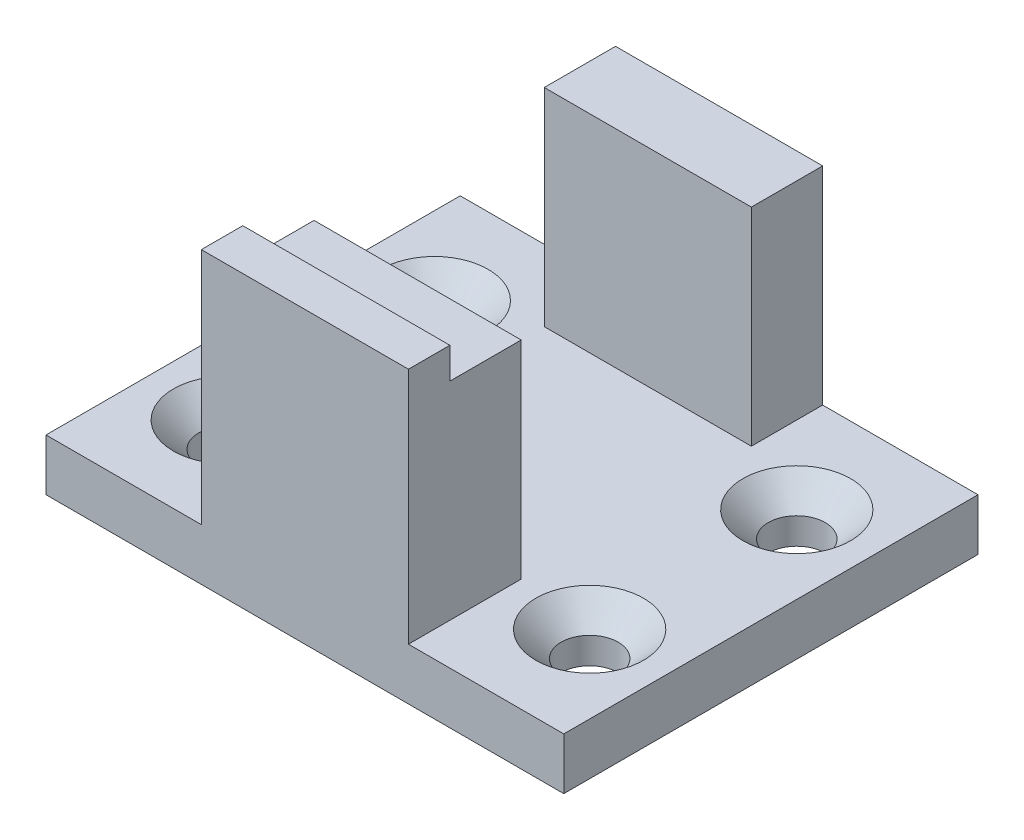
SolidWorks part; units mm, degrees
ref_plane "Front Plane" through (0, 0, 0) normal (0, 0, 1) x (1, 0, 0)
ref_plane "Top Plane" through (0, 0, 0) normal (0, 1, 0) x (1, 0, 0)
ref_plane "Right Plane" through (0, 0, 0) normal (1, 0, 0) x (0, 0, -1)
sketch "Sketch1" plane through (0, 0, 0) normal (0, 1, 0) x (1, 0, 0)
  line L1 (0, 0) -> (20, 0)
  line L2 (0, 0) -> (0, -40)
  line L3 (0, -40) -> (20, -40)
  line L4 (20, 0) -> (20, -40)
  dimension "D1" = 40
  dimension "D2" = 20
extrude "Boss-Extrude1" add sketch "Sketch1" along normal blind 25
sketch "Sketch2" plane through (0, 25, 0) normal (0, 1, 0) x (1, 0, 0)
  line L0 (20, -40) -> (20, 0) construction
  line L1 (0, -40) -> (20, -40)
  line L2 (0, -40) -> (0, -36)
  line L3 (0, -36) -> (20, -36)
  line L4 (20, -40) -> (20, -36)
  dimension "D1" = 4
extrude "Boss-Extrude2" add sketch "Sketch2" along normal blind 3
sketch "Sketch3" plane through (0, 0, 0) normal (-1, 0, 0) x (0, 0, 1)
  line L0 (0, 25) -> (36, 25) construction
  line L1 (0, 25) -> (36, 25)
  line L3 (6.885, 25) -> (29.115, 25)
  line L4 (6.885, 25) -> (6.885, 5)
  line L5 (6.885, 5) -> (29.115, 5)
  line L6 (29.115, 25) -> (29.115, 5)
  point P6 (18, 25)
  point P7 (18, 25)
  dimension "D1" = 22.23
  dimension "D2" = 20
extrude "Cut-Extrude1" cut sketch "Sketch3" against normal up to surface (20 mm away) contours L6 L1 L4 L5 up to face at (20, 17.6667, 25.3333)
sketch "Sketch4" plane through (0, 0, 0) normal (0, 1, 0) x (1, 0, 0)
  line L0 (0, 0) -> (0, -40) construction
  line L1 (0, 0) -> (0, -40)
  line L3 (0, 0) -> (-15, 0)
  line L4 (0, 0) -> (0, -40)
  line L5 (0, -40) -> (-15, -40)
  line L6 (-15, 0) -> (-15, -40)
  dimension "D1" = 15
extrude "Boss-Extrude3" add sketch "Sketch4" along normal up to surface (5 mm away) contours L3 L6 L5 L1 up to face at (10, 5, 18)
sketch "Sketch5" plane through (0, 5, 0) normal (0, 1, 0) x (1, 0, 0)
  line L0 (0, 0) -> (0, -40) construction
  line L1 (0, 0) -> (0, -40) construction
  line L2 (0, 0) -> (-15, 0) construction
  line L3 (-15, 0) -> (-15, -40) construction
  line L4 (0, -40) -> (-15, -40) construction
  line L5 (0, 0) -> (0, -40)
  line L6 (0, 0) -> (0, -40)
  line L7 (0, 0) -> (-15, 0)
  line L8 (-15, 0) -> (-15, -40)
  line L9 (0, -40) -> (-15, -40)
  line L10 (-7.5, 0) -> (-7.5, -10) construction
  line L11 (-7.5, -10) -> (-7.5, -20) construction
  line L12 (-7.5, -20) -> (-7.5, -30) construction
  line L13 (-7.5, -30) -> (-7.5, -40) construction
  point P2 (-7.5, -10)
  point P3 (-7.5, -30)
hole_wizard "CSK for M5 Countersunk Flat Head Screw1" positions "Sketch6" profile "Sketch8" countersink size "M5" standard "ISO" end condition through all
sketch "Sketch6" plane through (0, 5, 0) normal (0, 1, 0) x (1, 0, 0)
  point P0 (-7.5, -10)
  point P3 (-7.5, -30)
sketch "Sketch8" plane through (-7.5, 5, 10) normal (1, 0, 0) x (0, 0, 1)
  line L0 (0, 0) -> (0, 5)
  line L1 (0, 5) -> (2.75, 5)
  line L2 (2.75, 5) -> (2.75, 2.45)
  line L3 (2.75, 2.45) -> (5.2, 0)
  line L5 (5.2, 0) -> (0, 0)
  line L6 (-2.75, 2.45) -> (-5.2, 0) construction
  line L11 (0, -6.35) -> (0, 107.95) construction
  dimension "Thru Hole Dia." = 5.5
  dimension "Thru Hole Depth" = 5
  dimension "Near C'Sink Dia." = 10.4
  dimension "Near C'Sink Angle" = 90
ref_plane "Plane1" through (10, 0, 0) normal (-1, 0, 0) x (0, 0, 1)
mirror "Mirror1" about plane through (10, 0, 0) normal (-1, 0, 0) of "Boss-Extrude3", "CSK for M5 Countersunk Flat Head Screw1"
